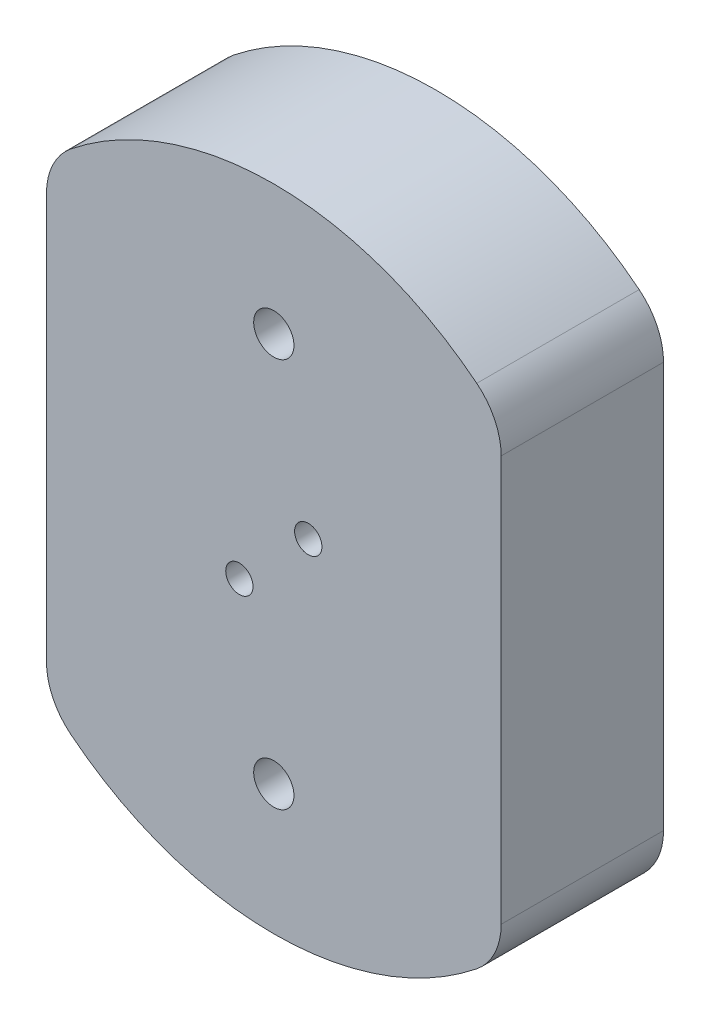
SolidWorks part; units mm, degrees
ref_plane "Front Plane" through (0, 0, 0) normal (0, 0, 1) x (1, 0, 0)
ref_plane "Top Plane" through (0, 0, 0) normal (0, 1, 0) x (1, 0, 0)
ref_plane "Right Plane" through (0, 0, 0) normal (1, 0, 0) x (0, 0, -1)
sketch "Sketch1" plane through (0, 0, 0) normal (0, 0, 1) x (1, 0, 0)
  line L0 (-8.9722, 12.0208) -> (8.9722, 12.0208)
  line L1 (-12.0208, 12.0208) -> (12.0208, 12.0208) construction
  line L2 (-12.0208, 12.0208) -> (-12.0208, -12.0208) construction
  line L3 (-12.0208, -12.0208) -> (12.0208, -12.0208) construction
  line L4 (12.0208, 12.0208) -> (12.0208, -12.0208) construction
  line L5 (-12.0208, 12.0208) -> (12.0208, -12.0208) construction
  line L6 (-12.0208, -12.0208) -> (12.0208, 12.0208) construction
  line L7 (-8.9722, -12.0208) -> (8.9722, -12.0208)
  line L8 (-12.0208, -8.9722) -> (-12.0208, 8.9722)
  line L9 (12.0208, -8.9722) -> (12.0208, 8.9722)
  circle A0 centre (0, 0) radius 50
  circle A1 centre (0, 0) radius 15 construction
  circle A2 centre (0, 0) radius 17 construction
  arc A3 (-12.0208, 8.9722) -> (-8.9722, 12.0208) centre (0, 0) cw
  arc A4 (8.9722, 12.0208) -> (12.0208, 8.9722) centre (0, 0) cw
  arc A5 (-12.0208, -8.9722) -> (-8.9722, -12.0208) centre (0, 0) ccw
  arc A6 (8.9722, -12.0208) -> (12.0208, -8.9722) centre (0, 0) ccw
  dimension "D1" = 100
  dimension "D2" = 30
  dimension "D3" = 34
extrude "Boss-Extrude1" add sketch "Sketch1" along normal blind 20
sketch "Sketch2" plane through (0, 0, 20) normal (0, 0, 1) x (1, 0, 0)
  circle A0 centre (0, 0) radius 50
extrude "Boss-Extrude2" add sketch "Sketch2" along normal blind 5
sketch "Sketch3" plane through (0, 0, 20) normal (0, 0, -1) x (-1, 0, 0)
  line L0 (0, 0) -> (-10.6066, 10.6066) construction
  line L1 (0, 0) -> (10.6066, -10.6066) construction
  arc A0 (-8.9722, 12.0208) -> (-12.0208, 8.9722) centre (0, 0) ccw construction
  arc A1 (8.9722, -12.0208) -> (12.0208, -8.9722) centre (0, 0) ccw construction
  circle A2 centre (-5.3033, 5.3033) radius 2.1
  circle A3 centre (5.3033, -5.3033) radius 2.1
  dimension "D1" = 4.2
extrude "Cut-Extrude1" cut sketch "Sketch3" against normal up to surface (5 mm away) up to face at (50, 0, 25)
sketch "Sketch4" plane through (0, 0, 0) normal (0, 0, -1) x (-1, 0, 0)
  line L0 (0, 0) -> (0, 30) construction
  line L1 (0, 0) -> (0, -30) construction
  circle A0 centre (0, 30) radius 3.1
  circle A1 centre (0, -30) radius 3.1
  dimension "D1" = 6.2
  dimension "D2" = 30
extrude "Cut-Extrude2" cut sketch "Sketch4" against normal through all
sketch "Sketch5" plane through (0, 0, 0) normal (0, 0, -1) x (-1, 0, 0)
  line L1 (5.8312, 30) -> (2.9156, 35.05)
  line L2 (2.9156, 35.05) -> (-2.9156, 35.05)
  line L3 (-2.9156, 35.05) -> (-5.8312, 30)
  line L4 (-5.8312, 30) -> (-2.9156, 24.95)
  line L5 (-2.9156, 24.95) -> (2.9156, 24.95)
  line L6 (2.9156, 24.95) -> (5.8312, 30)
  line L7 (5.8312, -30) -> (2.9156, -24.95)
  line L8 (2.9156, -24.95) -> (-2.9156, -24.95)
  line L9 (-2.9156, -24.95) -> (-5.8312, -30)
  line L10 (-5.8312, -30) -> (-2.9156, -35.05)
  line L11 (-2.9156, -35.05) -> (2.9156, -35.05)
  line L12 (2.9156, -35.05) -> (5.8312, -30)
  line L13 (-8.9722, 12.0208) -> (8.9722, 12.0208) construction
  circle A0 centre (0, 30) radius 5.05 construction
  circle A1 centre (0, -30) radius 5.05 construction
  dimension "D1" = 10.1
extrude "Cut-Extrude3" cut sketch "Sketch5" against normal blind 6
fillet "Fillet1" radius 0.5 12 edges at (0, -24.95, 0) (-4.3734, -27.475, 0) (-4.3734, -32.525, 0) (0, -35.05, 0) (4.3734, -32.525, 0) (4.3734, -27.475, 0) (0, 24.95, 0) (-4.3734, 27.475, 0) (-4.3734, 32.525, 0) (0, 35.05, 0) (4.3734, 32.525, 0) (4.3734, 27.475, 0)
sketch "Sketch6" plane through (0, 0, 0) normal (0, 0, -1) x (-1, 0, 0)
  line L0 (0, 0) -> (-35, 0) construction
  line L1 (-35, 0) -> (-35, 35.7071)
  line L2 (-35, 0) -> (-35, -35.7071)
  circle A0 centre (0, 0) radius 50 construction
  arc A1 (-35, -35.7071) -> (-35, 35.7071) centre (0, 0) cw
  dimension "D1" = 35
extrude "Cut-Extrude4" cut sketch "Sketch6" against normal through all
ref_plane "Plane1" through (0, 0, 0) normal (1, 0, 0) x (0, 0, -1)
mirror "Mirror1" about plane through (0, 0, 0) normal (1, 0, 0) of "Cut-Extrude4"
fillet "Fillet2" radius 10 4 edges at (35, 35.7071, 12.5) (35, -35.7071, 12.5) (-35, -35.7071, 12.5) (-35, 35.7071, 12.5)
